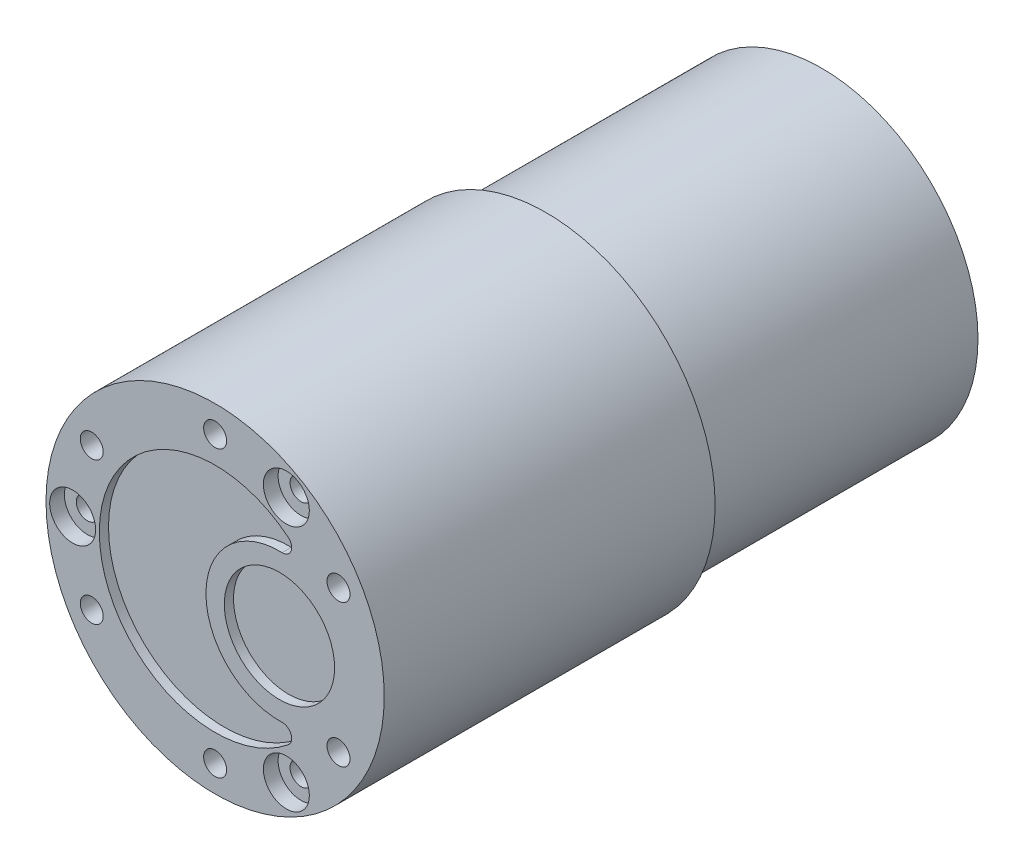
SolidWorks part; units mm, degrees
ref_plane "Alzado" through (0, 0, 0) normal (0, 0, 1) x (1, 0, 0)
ref_plane "Planta" through (0, 0, 0) normal (0, 1, 0) x (1, 0, 0)
ref_plane "Vista lateral" through (0, 0, 0) normal (1, 0, 0) x (0, 0, -1)
sketch "Croquis1" plane through (0, 0, 0) normal (1, 0, 0) x (0, 0, -1)
  line L0 (-33.5, 0) -> (33.5, 0)
  line L1 (32.5, 17) -> (32.5, 6)
  line L2 (32.5, 17) -> (2.5, 17)
  line L3 (2.5, 17) -> (2.5, 18.4)
  line L4 (2.5, 18.4) -> (-33.5, 18.4)
  line L5 (-33.5, 18.4) -> (-33.5, 0)
  line L6 (32.5, 6) -> (33.5, 5)
  line L7 (33.5, 5) -> (33.5, 0)
  dimension "D1" = 30
  dimension "D2" = 36
  dimension "D3" = 17
  dimension "D4" = 6
  dimension "D5" = 18.4
  dimension "D6" = 5
  dimension "D7" = 1
revolve "Revolución1" add sketch "Croquis1" angle 360 about L0
sketch "Croquis5" plane through (0, 0, 33.5) normal (0, 0, 1) x (1, 0, 0)
  line L0 (-15.5, 0) -> (15.5, 0) construction
  line L1 (-15.5, 0) -> (-13.4234, -7.75)
  line L2 (-13.4234, -7.75) -> (-7.75, -13.4234)
  line L3 (-7.75, -13.4234) -> (0, -15.5)
  line L4 (0, -15.5) -> (7.75, -13.4234)
  line L5 (7.75, -13.4234) -> (13.4234, -7.75)
  line L6 (13.4234, -7.75) -> (15.5, 0)
  line L7 (15.5, 0) -> (13.4234, 7.75)
  line L8 (13.4234, 7.75) -> (7.75, 13.4234)
  line L9 (7.75, 13.4234) -> (0, 15.5)
  line L10 (0, 15.5) -> (-7.75, 13.4234)
  line L11 (-7.75, 13.4234) -> (-13.4234, 7.75)
  line L12 (-13.4234, 7.75) -> (-15.5, 0)
  circle A0 centre (0, 0) radius 14.9719 construction
  dimension "D1" = 31
hole_wizard "Taladro roscado M3x0.52" positions "Croquis7" profile "Croquis6" tap size "M3x0.5" standard "Ansi Metric"
sketch "Croquis7" plane through (0, 0, 33.5) normal (0, 0, 1) x (1, 0, 0)
  point P29 (0, 15.5)
  point P32 (0, -15.5)
  point P38 (13.4234, -7.75)
  point P41 (13.4234, 7.75)
  point P47 (-13.4234, 7.75)
  point P53 (-13.4234, -7.75)
sketch "Croquis6" plane through (0, 15.5, 33.5) normal (1, 0, 0) x (0, -1, 0)
  line L0 (0, 0) -> (0, 9.2511)
  line L1 (0, 9.2511) -> (1.25, 8.5)
  line L2 (1.25, 8.5) -> (1.25, 0)
  line L5 (1.25, 0) -> (0, 0)
  line L10 (0, 9.2511) -> (-1.25, 8.5) construction
  line L11 (0, -6.35) -> (0, 107.95) construction
  dimension "Diámetro de perforador para roscar" = 2.5
  dimension "Profundidad de perforador para roscar" = 8.5
  dimension "Ángulo de perforador" = 118
hole_wizard "Refrentado para tornillo con cabeza troncocónica de M21" positions "Croquis10" profile "Croquis11" counterbore size "M2" standard "Ansi Metric"
sketch "Croquis10" plane through (0, 0, 33.5) normal (0, 0, 1) x (1, 0, 0)
  point P0 (-15.5, 0)
  point P3 (7.75, 13.4234)
  point P6 (7.75, -13.4234)
sketch "Croquis11" plane through (-15.5, 0, 33.5) normal (1, 0, 0) x (0, -1, 0)
  line L0 (0, 0) -> (0, 5.721)
  line L1 (0, 5.721) -> (1.2, 5)
  line L2 (1.2, 5) -> (1.2, 1.6)
  line L3 (1.2, 1.6) -> (2.5, 1.6)
  line L4 (2.5, 1.6) -> (2.5, 0)
  line L5 (2.5, 0) -> (0, 0)
  line L10 (0, 5.721) -> (-1.2, 5) construction
  line L11 (0, -6.35) -> (0, 107.95) construction
  dimension "Diámetro de taladro" = 2.4
  dimension "Profundidad de taladro" = 5
  dimension "Diámetro de refrentado" = 5
  dimension "Profundidad de refrentado" = 1.6
  dimension "Ángulo de perforador" = 118
sketch "Croquis8" plane through (0, 0, 33.5) normal (0, 0, 1) x (1, 0, 0)
  line L0 (-12.6, 0) -> (-15.5, 0) construction
  line L1 (-15.5, 0) -> (-18.4, 0) construction
  line L2 (-1, 0) -> (7, 0) construction
  line L3 (-15.5, 0) -> (15.5, 0) construction
  arc A0 (7.9572, 9.7695) -> (7.9572, -9.7695) centre (0, 0) ccw
  arc A1 (7.2895, -7.9948) -> (7.2895, 7.9948) centre (7, 0) cw
  arc A2 (7.9572, -9.7695) -> (7.2895, -7.9948) centre (7.3257, -8.9941) ccw
  arc A3 (7.2895, 7.9948) -> (7.9572, 9.7695) centre (7.3257, 8.9941) ccw
  circle A4 centre (0, 0) radius 18.4 construction
  circle A5 centre (7, 0) radius 6
  point P12 (7, 0)
  dimension "D2" = 1
  dimension "D3" = 7
  dimension "D4" = 12
  dimension "D1" = 8
extrude "Cortar-Extruir2" cut sketch "Croquis8" against normal blind 1
